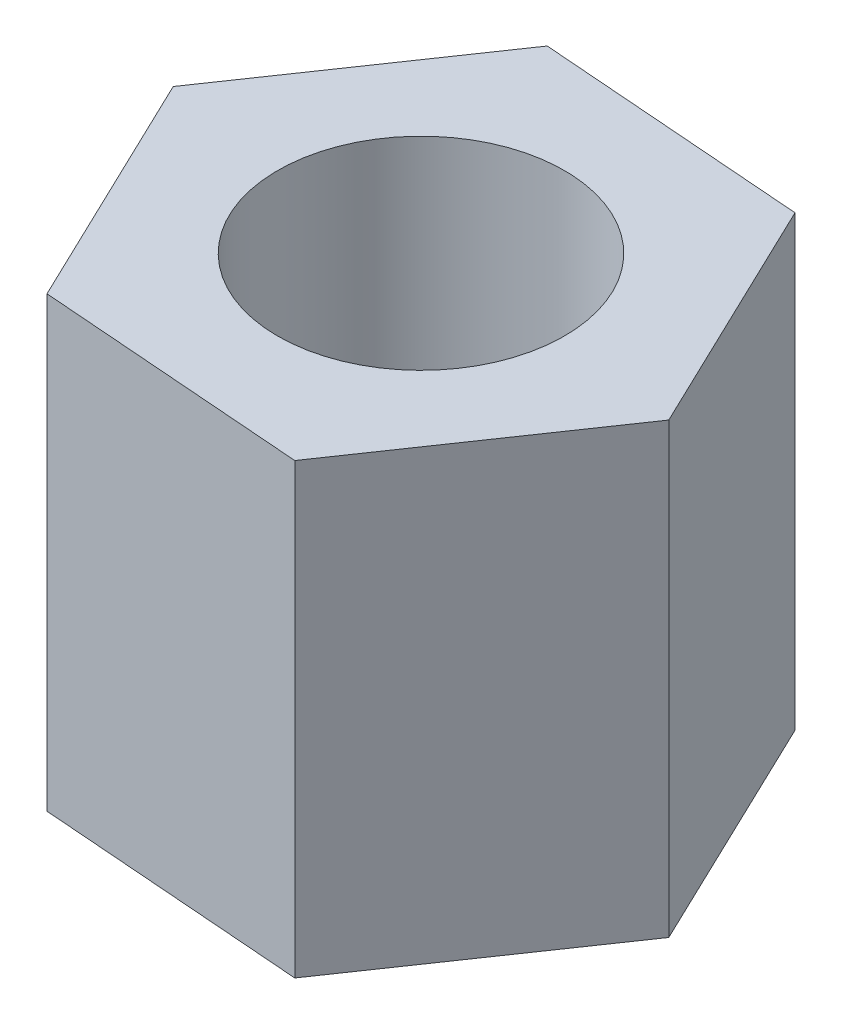
SolidWorks part; units mm, degrees
ref_plane "前视基准面" through (0, 0, 0) normal (0, 0, 1) x (1, 0, 0)
ref_plane "上视基准面" through (0, 0, 0) normal (0, 1, 0) x (1, 0, 0)
ref_plane "右视基准面" through (0, 0, 0) normal (1, 0, 0) x (0, 0, -1)
other "Configuration Table"
sketch "草图1" plane through (0, 0, 0) normal (0, 1, 0) x (1, 0, 0)
  line L1 (1.2984, -2.7069) -> (2.9935, -0.229)
  line L2 (2.9935, -0.229) -> (1.695, 2.4779)
  line L3 (1.695, 2.4779) -> (-1.2984, 2.7069)
  line L4 (-1.2984, 2.7069) -> (-2.9935, 0.229)
  line L5 (-2.9935, 0.229) -> (-1.695, -2.4779)
  line L6 (-1.695, -2.4779) -> (1.2984, -2.7069)
  circle A0 centre (0, 0) radius 2.6 construction
  circle A1 centre (0, 0) radius 1.6
  dimension "D1" = 5.2
  dimension "D2" = 3.2
extrude "凸台-拉伸1" add sketch "草图1" along normal blind 5
